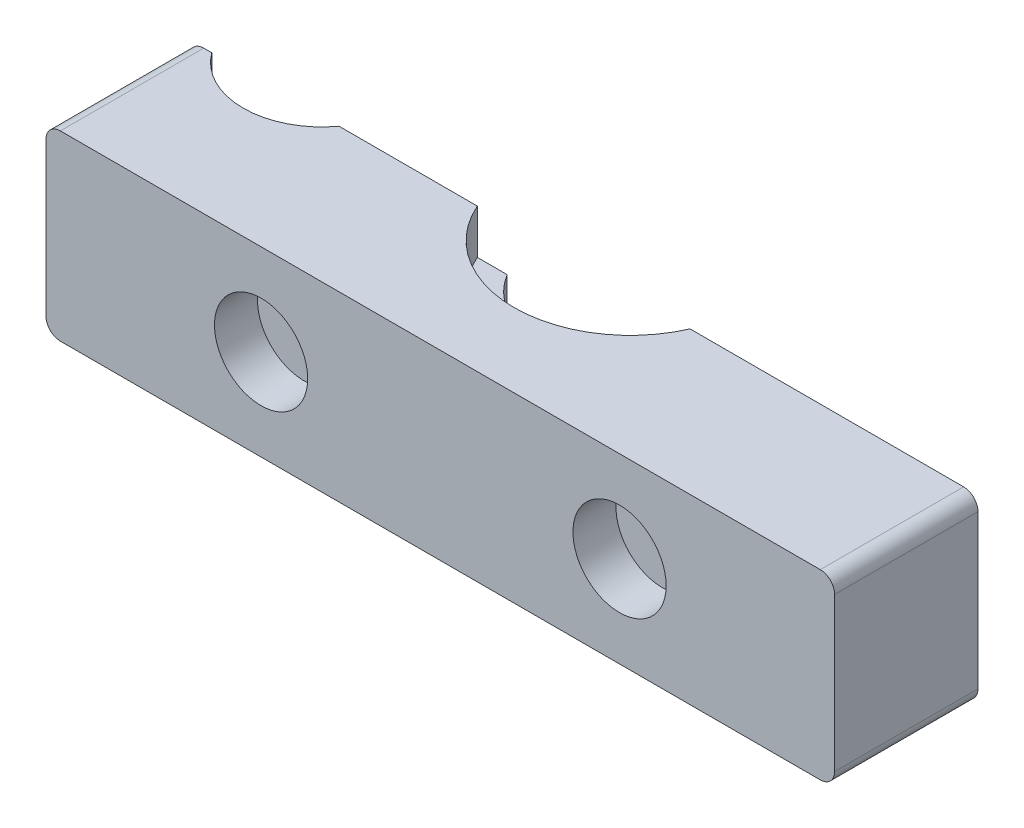
SolidWorks part; units mm, degrees
ref_plane "XY" through (0, 0, 0) normal (0, 0, 1) x (1, 0, 0)
ref_plane "XZ" through (0, 0, 0) normal (0, 1, 0) x (1, 0, 0)
ref_plane "YZ" through (0, 0, 0) normal (1, 0, 0) x (0, 0, -1)
sketch "Sketch1" plane through (0, 0, 0) normal (0, 0, 1) x (1, 0, 0)
  line L1 (27.5, 6.35) -> (-27.5, 6.35)
  line L2 (27.5, 6.35) -> (27.5, -6.35)
  line L3 (27.5, -6.35) -> (-27.5, -6.35)
  line L4 (-27.5, 6.35) -> (-27.5, -6.35)
  line L5 (27.5, 6.35) -> (-27.5, -6.35) construction
  line L6 (27.5, -6.35) -> (-27.5, 6.35) construction
  point P0 (0, 0)
  dimension "D1" = 55
  dimension "D2" = 12.7
extrude "Boss-Extrude1" add sketch "Sketch1" along normal blind 10
sketch "Sketch2" plane through (0, 6.35, 0) normal (0, 1, 0) x (1, 0, 0)
  line L0 (27.5, -10) -> (-27.5, -10) construction
  line L1 (27.5, 0) -> (-27.5, 0) construction
  line L2 (5.3385, 0) -> (-5.3385, 0)
  line L3 (-17.0629, 0) -> (-25.9371, 0)
  arc A0 (-25.9371, 0) -> (-17.0629, 0) centre (-21.5, 3.25) ccw
  arc A1 (-5.3385, 0) -> (5.3385, 0) centre (0, 3.25) ccw
  dimension "D1" = 12.5
  dimension "D3" = 11
  dimension "D2" = 13.25
  dimension "D4" = 13.25
  dimension "D5" = 21.5
extrude "Cut-Extrude1" cut sketch "Sketch2" against normal through all
sketch "Sketch3" plane through (0, 0, 0) normal (0, 0, -1) x (-1, 0, 0)
  line L1 (5.3385, -6.35) -> (7.42, -6.35)
  line L2 (5.3385, -6.35) -> (5.3385, -2.35)
  line L3 (5.3385, -2.35) -> (7.42, -2.35)
  line L4 (7.42, -6.35) -> (7.42, -2.35)
  line L5 (5.3385, 6.35) -> (7.42, 6.35)
  line L6 (5.3385, 6.35) -> (5.3385, 3.25)
  line L7 (5.3385, 3.25) -> (7.42, 3.25)
  line L8 (7.42, 6.35) -> (7.42, 3.25)
  dimension "D1" = 4
  dimension "D2" = 3.1
  dimension "D3" = 7.42
sketch "Sketch4" plane through (0, -6.35, 0) normal (0, -1, 0) x (1, 0, 0)
  arc A0 (5.3385, 0) -> (-5.3385, 0) centre (0, -3.25) ccw construction
  arc A1 (5.3385, 0) -> (-5.3385, 0) centre (0, -3.25) ccw
ref_plane "Plane1" through (0, 0, -3.25) normal (0, 0, -1) x (-1, 0, 0)
sketch "Sketch6" plane through (0, 0, -3.25) normal (0, 0, -1) x (-1, 0, 0)
  line L0 (5.3385, 6.35) -> (-5.3385, 6.35) construction
  line L1 (0, 6.35) -> (8.1, 6.35)
  line L2 (0, 6.35) -> (0, 3.25)
  line L3 (0, 3.25) -> (8.1, 3.25)
  line L4 (8.1, 6.35) -> (8.1, 3.25)
  line L5 (0, -6.35) -> (0, 6.35) construction
  line L6 (5.3385, 3.25) -> (7.42, 3.25) construction
  line L7 (-5.3385, -6.35) -> (5.3385, -6.35) construction
  line L8 (0, -6.35) -> (8.1, -6.35)
  line L9 (0, -6.35) -> (0, -2.35)
  line L10 (0, -2.35) -> (8.1, -2.35)
  line L11 (8.1, -6.35) -> (8.1, -2.35)
  line L12 (5.3385, -2.35) -> (7.42, -2.35) construction
  dimension "D1" = 8.1
revolve "Cut-Revolve1" cut sketch "Sketch6" angle 360 about axis through (0, -6.35, -3.25) along (0, 1, 0)
sketch "Sketch7" plane through (0, 0, 0) normal (0, 0, -1) x (-1, 0, 0)
  line L0 (0, 10.1464) -> (0, -10.4998) construction
  line L1 (7.4194, 6.35) -> (17.0629, 6.35) construction
  circle A0 centre (12.5, 0) radius 1.75
  circle A1 centre (-12.5, 0) radius 1.75
  dimension "D1" = 6.35
  dimension "D3" = 3.5
  dimension "D2" = 12.5
extrude "Cut-Extrude2" cut sketch "Sketch7" against normal blind 6.5
sketch "Sketch8" plane through (0, 0, 10) normal (0, 0, 1) x (1, 0, 0)
  circle A0 centre (-12.5, 0) radius 3.25
  circle A1 centre (12.5, 0) radius 3.25
  circle A2 centre (-12.5, 0) radius 1.75 construction
  circle A3 centre (12.5, 0) radius 1.75 construction
  dimension "D1" = 6.5
extrude "Cut-Extrude3" cut sketch "Sketch8" against normal blind 3
fillet "Fillet1" radius 1 4 edges at (-27.5, 6.35, 5) (27.5, 6.35, 5) (27.5, -6.35, 5) (-27.5, -6.35, 5)
